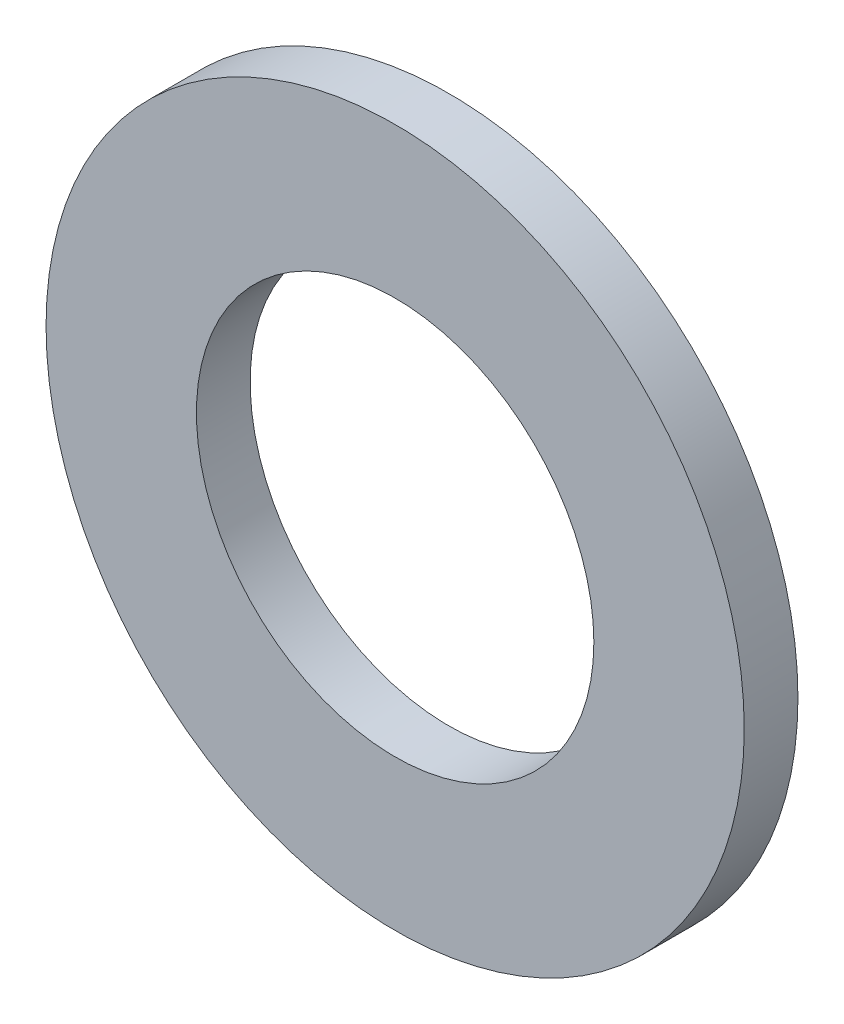
SolidWorks part; units mm, degrees
material "45"
ref_plane "前视基准面" through (0, 0, 0) normal (0, 0, 1) x (1, 0, 0)
ref_plane "上视基准面" through (0, 0, 0) normal (0, 1, 0) x (1, 0, 0)
ref_plane "右视基准面" through (0, 0, 0) normal (1, 0, 0) x (0, 0, -1)
sketch "草图1" plane through (0, 0, 0) normal (0, 0, 1) x (1, 0, 0)
  circle A0 centre (0, 0) radius 32.5
  circle A1 centre (0, 0) radius 18.5
  dimension "D1" = 65
  dimension "D2" = 37
extrude "凸台-拉伸1" add sketch "草图1" along normal blind 5
